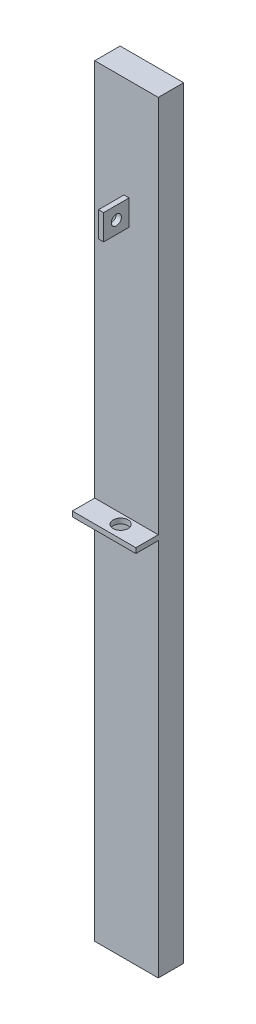
SolidWorks part; units mm, degrees
ref_plane "Front Plane" through (0, 0, 0) normal (0, 0, 1) x (1, 0, 0)
ref_plane "Top Plane" through (0, 0, 0) normal (0, 1, 0) x (1, 0, 0)
ref_plane "Right Plane" through (0, 0, 0) normal (1, 0, 0) x (0, 0, -1)
sketch "Sketch1" plane through (0, 0, 0) normal (0, 0, 1) x (1, 0, 0)
  line L0 (-34.4118, 27.5) -> (-9.4118, 27.5)
  line L1 (-9.4118, 27.5) -> (-9.4118, -272.5)
  line L2 (-9.4118, -272.5) -> (-34.4118, -272.5)
  line L3 (-34.4118, -272.5) -> (-34.4118, 27.5)
  line L4 (-32.9118, 26) -> (-10.9118, 26)
  line L5 (-10.9118, 26) -> (-10.9118, -271)
  line L6 (-10.9118, -271) -> (-32.9118, -271)
  line L7 (-32.9118, -271) -> (-32.9118, 26)
  dimension "D1" = 25
  dimension "D2" = 300
  dimension "D3" = 1.5
extrude "Boss-Extrude1" add sketch "Sketch1" along normal blind 10
ref_plane "Plane1" through (-32.9118, 26, 10) normal (-1, 0, 0) x (0, 0, 1)
sketch "Sketch3" plane through (0, 0, 10) normal (0, 0, 1) x (1, 0, 0)
  line L0 (-32.9118, 26) -> (-10.9118, 26)
  line L1 (-32.9118, 32.05) -> (-32.9118, 19.95) construction
  line L2 (-10.9118, 26) -> (-32.9118, 26) construction
  line L3 (-10.9118, 26) -> (-10.9118, -271)
  line L4 (-10.9118, -271) -> (-32.9118, -271)
  line L5 (-32.9118, -271) -> (-32.9118, 26)
extrude "Boss-Extrude2" add sketch "Sketch3" against normal blind 1.5
sketch "Sketch6" plane through (-34.4118, 0, 0) normal (-1, 0, 0) x (0, 0, 1)
  line L0 (10, -121.5) -> (18.8206, -121.5)
  line L1 (10, 27.5) -> (10, -272.5) construction
  line L2 (18.8206, -121.5) -> (18.8206, -123.5)
  line L3 (18.8206, -123.5) -> (10, -123.5)
  line L4 (10, 27.5) -> (0, 27.5) construction
  line L5 (10, -272.5) -> (10, -123.5)
  line L9 (0, 27.5) -> (0, -272.5)
  line L10 (0, -272.5) -> (10, -272.5)
  line L11 (10, -272.5) -> (10, 27.5)
  line L12 (10, 27.5) -> (0, 27.5)
  line L13 (0, 27.5) -> (0, -272.5)
  line L14 (0, -272.5) -> (10, -272.5)
  line L15 (10, -121.5) -> (10, 27.5)
  line L16 (10, 27.5) -> (0, 27.5)
  dimension "D1" = 149
  dimension "D2" = 2
  dimension "D3" = 0
extrude "Boss-Extrude3" add sketch "Sketch6" against normal blind 25
sketch "Sketch7" plane through (0, -123.5, 0) normal (0, -1, 0) x (1, 0, 0)
  line L0 (-32.9118, 65) -> (-32.9118, -45) construction
  line L4 (-9.4118, 18.8206) -> (-34.4118, 18.8206) construction
  circle A0 centre (-20.4118, 13.8206) radius 2.9593
  dimension "D1" = 12.5
  dimension "D2" = 5
extrude "Cut-Extrude1" cut sketch "Sketch7" against normal blind 2
sketch "Sketch9" plane through (0, 0, 10) normal (0, 0, 1) x (1, 0, 0)
  line L0 (-14.6045, -22.5) -> (-22.9118, -22.5)
  line L1 (-22.9118, -22.5) -> (-22.9118, -12.5)
  line L2 (-22.9118, -12.5) -> (-20.9118, -12.5)
  line L3 (-20.9118, -12.5) -> (-20.9118, -22.5)
  line L4 (-9.4118, 27.5) -> (-34.4118, 27.5) construction
  line L5 (-9.4118, -121.5) -> (-9.4118, 27.5) construction
  point P7 (-21.9118, 27.5)
  point P8 (-21.9118, -12.5)
  dimension "D1" = 2
  dimension "D2" = 40
  dimension "D3" = 10
  dimension "D4" = 11.5
extrude "Boss-Extrude4" add sketch "Sketch9" along normal blind 10 contours L3 L2 L1 L0
sketch "Sketch10" plane through (-34.4118, 0, 0) normal (-1, 0, 0) x (0, 0, 1)
  line L0 (20, -22.5) -> (20, -12.5) construction
  circle A0 centre (15, -17.5) radius 2
  dimension "D1" = 5
extrude "Cut-Extrude2" cut sketch "Sketch10" against normal blind 15
sketch "Sketch11" plane through (0, 0, 0) normal (0, 0, -1) x (-1, 0, 0)
  line L4 (10.9118, 26) -> (10.9118, -271)
  line L5 (10.9118, -271) -> (32.9118, -271)
  line L6 (32.9118, -271) -> (32.9118, 26)
  line L7 (32.9118, 26) -> (10.9118, 26)
extrude "Cut-Extrude7" cut sketch "Sketch11" against normal blind 8
